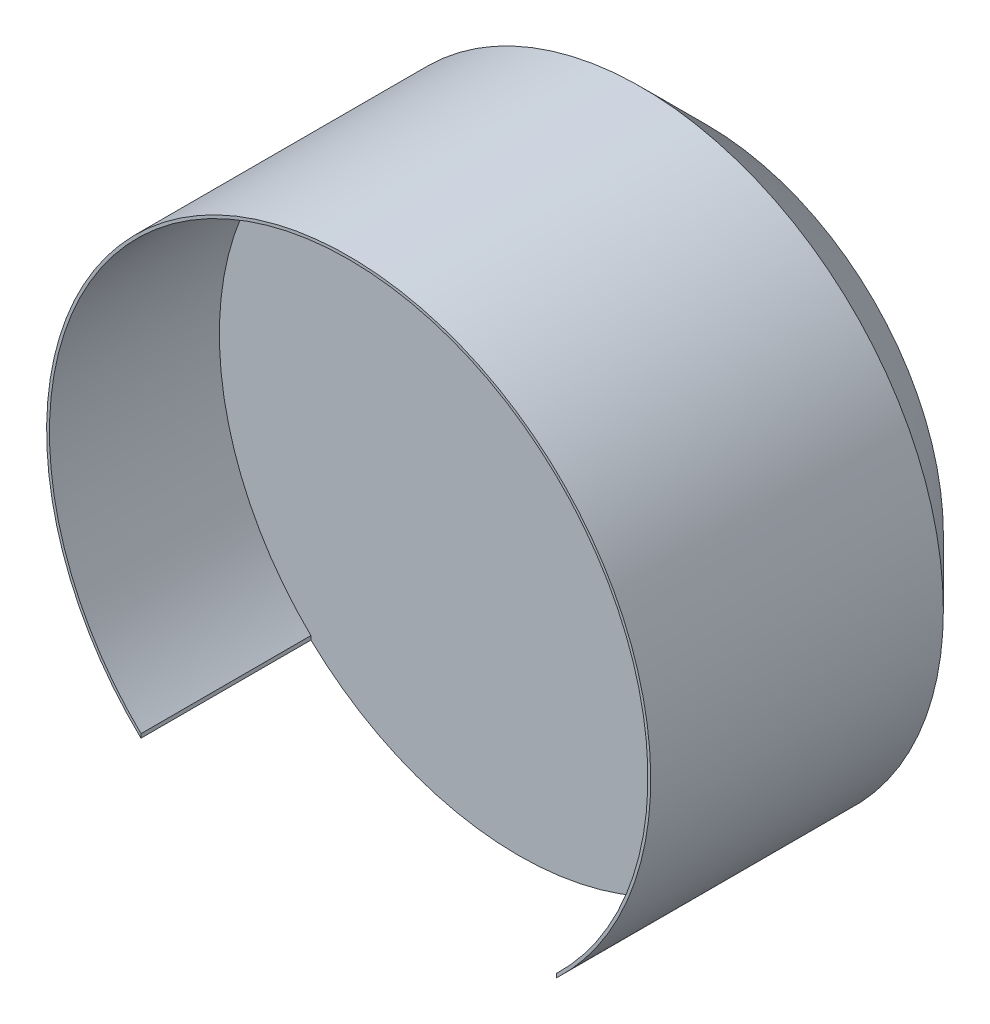
SolidWorks part; units mm, degrees
ref_plane "Plan de face" through (0, 0, 0) normal (0, 0, 1) x (1, 0, 0)
ref_plane "Plan de dessus" through (0, 0, 0) normal (0, 1, 0) x (1, 0, 0)
ref_plane "Plan de droite" through (0, 0, 0) normal (1, 0, 0) x (0, 0, -1)
sketch "Esquisse1" plane through (0, 0, 0) normal (0, 0, 1) x (1, 0, 0)
  circle A0 centre (0, 0) radius 320
  dimension "D1" = 640
extrude "Boss.-Extru.1" add sketch "Esquisse1" along normal blind 200
chamfer "Chanfrein2" distance 70 angle 45 1 edges at (320, 0, 0)
sketch "Esquisse2" plane through (0, 0, 200) normal (0, 0, 1) x (1, 0, 0)
  circle A0 centre (0, 0) radius 320
  circle A1 centre (0, 0) radius 317
  circle A2 centre (0, 0) radius 320 construction
  dimension "D1" = 3
extrude "Boss.-Extru.2" add sketch "Esquisse2" along normal blind 180
sketch "Esquisse3" plane through (0, 0, 0) normal (0, 1, 0) x (1, 0, 0)
  line L0 (-320, -380) -> (320, -380) construction
  line L1 (220, -200) -> (-220, -200)
  line L2 (220, -200) -> (220, -380)
  line L3 (220, -380) -> (-220, -380)
  line L4 (-220, -200) -> (-220, -380)
  point P5 (0, -380)
  dimension "D1" = 180
  dimension "0" = 440
extrude "Enlèv. mat.-Extru.1" cut sketch "Esquisse3" against normal through all
